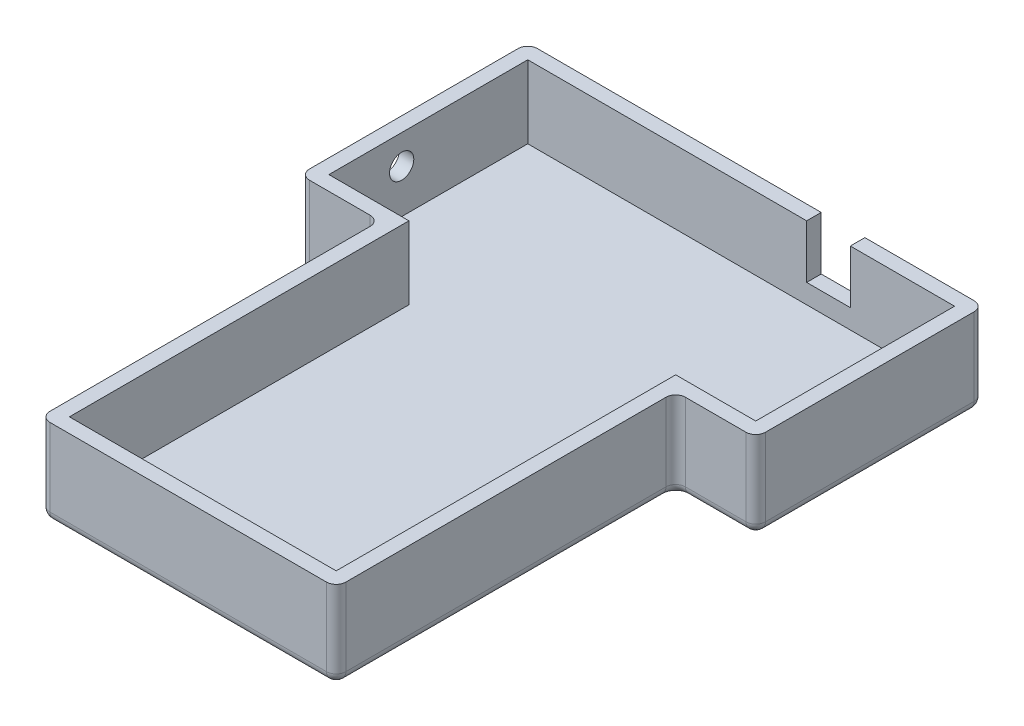
SolidWorks part; units mm, degrees
material "PEI"
ref_plane "Front Plane" through (0, 0, 0) normal (0, 0, 1) x (1, 0, 0)
ref_plane "Top Plane" through (0, 0, 0) normal (0, 1, 0) x (1, 0, 0)
ref_plane "Right Plane" through (0, 0, 0) normal (1, 0, 0) x (0, 0, -1)
sketch "Sketch1" plane through (0, 0, 0) normal (0, 1, 0) x (1, 0, 0)
  line L0 (0, 0) -> (88, 0)
  line L1 (88, 0) -> (88, -41)
  line L2 (88, -41) -> (71.5, -41)
  line L3 (71.5, -41) -> (71.5, -111)
  line L4 (71.5, -111) -> (16.5, -111)
  line L5 (16.5, -111) -> (16.5, -41)
  line L6 (16.5, -41) -> (0, -41)
  line L7 (0, -41) -> (0, 0)
  dimension "D1" = 88
  dimension "D2" = 55
  dimension "D3" = 41
  dimension "D4" = 70
extrude "Boss-Extrude1" add sketch "Sketch1" along normal blind 15
shell "Shell1" thickness 3
sketch "Sketch3" plane through (0, 0, -3) normal (0, 0, -1) x (-1, 0, 0)
  line L0 (-91, 6) -> (3, 6) construction
  line L1 (-91, 15) -> (-91, -3) construction
  line L2 (3, 15) -> (3, -3) construction
  line L3 (-44, 6) -> (-44, -3) construction
  line L4 (-91, -3) -> (3, -3) construction
  line L5 (-44, -3) -> (-44, 15) construction
  line L6 (-91, 15) -> (3, 15) construction
  line L8 (-66.5, 15) -> (-57.5, 15)
  line L9 (-66.5, 15) -> (-66.5, 4)
  line L10 (-66.5, 4) -> (-57.5, 4)
  line L11 (-57.5, 15) -> (-57.5, 4)
  line L12 (-66.5, 15) -> (-57.5, 4) construction
  line L13 (-66.5, 4) -> (-57.5, 15) construction
  point P13 (-62, 9.5)
  point P18 (-44, 1.5)
  dimension "D1" = 11
  dimension "D2" = 9
  dimension "D3" = 13.5
  dimension "D4" = 0
extrude "Cut-Extrude1" cut sketch "Sketch3" against normal blind 3
sketch "Sketch4" plane through (-3, 0, 0) normal (-1, 0, 0) x (0, 0, 1)
  line L0 (44, 15) -> (44, -3) construction
  line L1 (-3, 15) -> (44, 15) construction
  circle A0 centre (26, 9) radius 2.5
  dimension "D1" = 5
  dimension "D2" = 18
  dimension "D3" = 6
extrude "Cut-Extrude2" cut sketch "Sketch4" against normal blind 3
fillet "Fillet1" radius 2 16 edges at (5.25, -3, 44) (13.5, -3, 79) (44, -3, 114) (74.5, -3, 79) (82.75, -3, 44) (91, -3, 20.5) (44, -3, -3) (-3, -3, 20.5) (-3, 6, -3) (91, 6, -3) (91, 6, 44) (74.5, 6, 44) (74.5, 6, 114) (13.5, 6, 114) (13.5, 6, 44) (-3, 6, 44)
